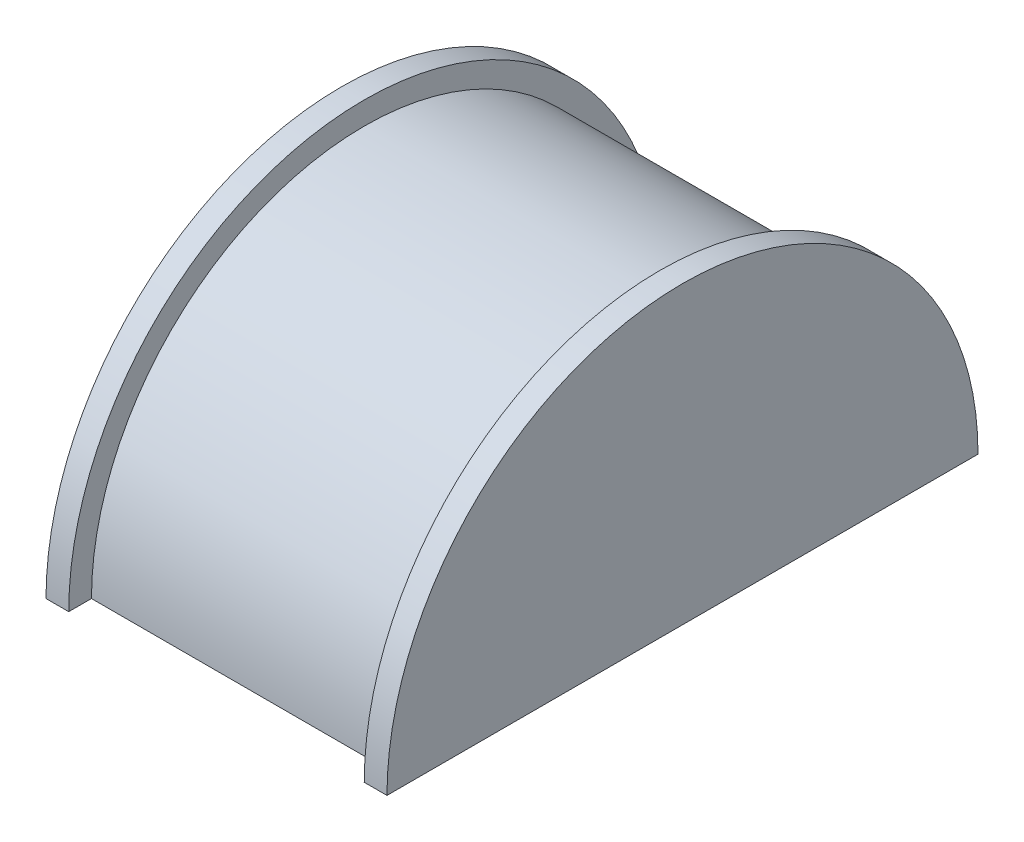
SolidWorks part; units mm, degrees
ref_plane "Front Plane" through (0, 0, 0) normal (0, 0, 1) x (1, 0, 0)
ref_plane "Top Plane" through (0, 0, 0) normal (0, 1, 0) x (1, 0, 0)
ref_plane "Right Plane" through (0, 0, 0) normal (1, 0, 0) x (0, 0, -1)
sketch "Sketch2" plane through (0, 0, 0) normal (1, 0, 0) x (0, 0, -1)
  line L0 (-6, 0) -> (6, 0)
  arc A0 (6, 0) -> (-6, 0) centre (0, 0) ccw
  dimension "D1" = 12
extrude "Boss-Extrude1" add sketch "Sketch2" along normal blind 6.5
ref_plane "Plane1" through (3.25, 0, 0) normal (1, 0, 0) x (0, 0, -1)
sketch "Sketch3" plane through (6.5, 0, 0) normal (1, 0, 0) x (0, 0, -1)
  line L0 (-6, 0) -> (6, 0) construction
  line L1 (-6.5, 0) -> (6.5, 0)
  arc A0 (6.5, 0) -> (-6.5, 0) centre (0, 0) ccw
  arc A1 (6, 0) -> (-6, 0) centre (0, 0) ccw construction
  dimension "D1" = 0.5
extrude "Boss-Extrude2" add sketch "Sketch3" along normal blind 0.5
mirror "Mirror1" about plane through (3.25, 0, 0) normal (1, 0, 0) of "Boss-Extrude2"
sketch "Sketch4" plane through (0, 0, 0) normal (0, -1, 0) x (1, 0, 0)
  line L0 (3.25, -6) -> (3.25, 6) construction
  line L1 (6.5, -6) -> (0, -6) construction
  line L2 (6.5, 6) -> (0, 6) construction
  circle A0 centre (3.25, 0) radius 1.9
  dimension "D1" = 3.8
extrude "Cut-Extrude1" cut sketch "Sketch4" against normal blind 5
equation "\"X-ROD-SPACING\"=45"
equation "\"Y-ROD-SPACING\"=75"
equation "\"Z-ROD-SPACING\"=17.5"
equation "\"Y-BED-OFFSET\"=2"
equation "\"Y-BED-ROD-INSET\"=3.5"
equation "\"Y-BED-SCREW-SPACING\"=209"
equation "\"Y-BED-SCREW-CUTOUT-SLOT-HEIGHT\"=2.5"
equation "\"T-SLOT-NUT-FILLET-RADIUS\"=0.5"
equation "\"T-SLOT-SCREW-SHAFT-RADIUS\"=1.55"
equation "\"T-SLOT-SCREW-SHAFT-CUTOUT-LENGTH\"=11"
equation "\"T-SLOT-NUT-DEPTH\"=3.5"
equation "\"T-SLOT-NUT-WIDTH\"=2.85"
equation "\"T-SLOT-NUT-END-DISTANCE\"=8"
equation "\"ACRYLIC-THICKNESS\"=10"
equation "\"ACRYLIC-THICKNESS2\"=4.5"
equation "\"ACRYLIC-TAB-CUTOUT-SIZE\"=\"ACRYLIC-THICKNESS\"+\"ACRYLIC-TAB-TOLERANCE\"*2"
equation "\"ACRYLIC-TAB-TOLERANCE\"=-.05"
equation "\"KERF\"=0.075"
equation "\"ACRYLIC-THICKNESS-TAB-CUTOUT-WIDTH\"=\"ACRYLIC-THICKNESS\"-\"KERF\"*2"
equation "\"ACRYLIC-THICKNESS-TAB-CUTOUT-HEIGHT\"=\"ACRYLIC-TAB-WIDTH\"-\"KERF\"*4"
equation "\"ACRYLIC-THICKNESS2-TAB-CUTOUT-WIDTH\"=\"ACRYLIC-THICKNESS2\"-\"KERF\"*2"
equation "\"ACRYLIC-THICKNESS2-TAB-CUTOUT-HEIGHT\"=\"ACRYLIC-TAB-WIDTH\"-\"KERF\"*4"
equation "\"ACRYLIC-TAB-WIDTH\"=\"ACRYLIC-THICKNESS\""
equation "\"ACRYLIC-M3-HOLE\"=2.9"
equation "\"SMOOTHROD-CAP-SCREW-DISTANCE\"=20"
equation "\"FRAME-WIDTH-INNER\"=370"
equation "\"NEMA17-HOLE-SPACING\"=31"
equation "\"NEMA17-CENTRAL-CUTOUT\"=22.5"
equation "\"Z-BRACKET-REACH\"=57"
equation "\"Z-ROD-INSET\"=13.5"
equation "\"TOP-BRACKET-SPACING\"=40"
equation "\"SMOOTHROD-X-LENGTH\"=350"
equation "\"SMOOTHROD-Y-LENGTH\"=350"
equation "\"SMOOTHROD-Z-LENGTH\"=350"
equation "\"SMOOTHROD-TIGHTENING-HEADROOM\"=.25"
equation "\"LEADSCREW-Z-LENGTH\"=300"
equation "\"SCREW-LENGTH-FRAME\"=\"ACRYLIC-THICKNESS\" + 10"
equation "\"SCREW-LENGTH-MOTOR\"=\"ACRYLIC-THICKNESS\" + 5"
equation "\"SCREW-LENGTH-EXTRUDER\"=28"
equation "\"SCREW-HEAD-RADIUS\"=6"
equation "\"PRINTED-M3-HOLE\"=3.5"
equation "\"PRINTED-X-SMOOTHROD-DIAMETER\"=8.8"
equation "\"PRINTED-X-SMOOTHROD-CUTOUT\"=10"
equation "\"PRINTED-X-BASE-HEIGHT\"=10"
equation "\"PRINTED-LM8UU-CUTOUT-SIZE\"=15.5"
equation "\"PRINTED-LM8UU-CUTOUT-LENGTH\"=24.5"
equation "\"PRINTED-X-IDLER-HEIGHT\"=16"
equation "\"PRINTED-M3-NUT-AF\"=6.25"
equation "\"PSU-MOUNTING-WIDTH\"=95"
equation "\"PSU-MOUNTING-HEIGHT\"=177"
equation "\"Y-BELT-TO-ROD-DISTANCE\"=20"
equation "\"SPOOL-HOLDER-ROD-SPACING\"=150"
equation "\"ACRYLIC-X-CARRIAGE-WIDTH\"=55"
equation "\"ACRYLIC-X-CARRIAGE-HEIGHT\"=75"
equation "\"ACRYLIC-X-CARRIAGE-LM8UU-CUTOUT-WIDTH\"=24.25"
equation "\"ACRYLIC-X-CARRIAGE-LM8UU-CUTOUT-HEIGHT\"=11.0"
equation "\"ACRYLIC-X-CARRIAGE-SCREW-SPACING-X\"=15"
equation "\"ACRYLIC-X-CARRIAGE-SCREW-SPACING-Y\"=33"
equation "\"ACRYLIC-X-CARRIAGE-CENTER-TAB-SPACING\"=14"
equation "\"ACRYLIC-X-CARRIAGE-EXTRUDER-OFFSET\"=26"
equation "\"ACRYLIC-X-CARRIAGE-EXTRUDER-ANGLE\"=90"
equation "\"ACRYLIC-X-CARRIAGE-EXTRUDER-SHELF-DEPTH\"=\"ACRYLIC-X-CARRIAGE-EXTRUDER-OFFSET\" + 28"
equation "\"ACRYLIC-X-CARRIAGE-EXTRUDER-BRACE-SPACING\"=23"
equation "\"ACRYLIC-X-CARRIAGE-EXTRUDER-BRACE-TAB-OFFSET\"=20"
equation "\"ACRYLIC-X-CARRIAGE-EXTRUDER-BRACE-HEIGHT\"=35"
equation "\"ACRYLIC-X-CARRIAGE-EXTRUDER-BRACE-SCREW-SPACING\"=22"
equation "\"ACRYLIC-X-CARRIAGE-DUAL-WIDTH-MULTIPLIER\"=1.65"
equation "\"ACRYLIC-X-CARRIAGE-DUAL-HOTEND-SPACING\"=42"
equation "\"ACRYLIC-X-CARRIAGE-DUAL-WIDTH\"=75"
equation "\"ACRYLIC-X-CARRIAGE-DUAL-FAN-OFFSET\"=52"
equation "\"ACRYLIC-X-CARRIAGE-DUAL-FAN-HEIGHT\"=20"
equation "\"ACRYLIC-X-CARRIAGE-DUAL-HOTEND-SEPARATION\"=36"
equation "\"ACRYLIC-X-CARRIAGE-DUAL-MOUNT-PLATE-DEPTH\"=75"
equation "\"ACRYLIC-X-CARRIAGE-DUAL-MOUNT-BRACE-WIDTH\"=33"
equation "\"ACRYLIC-X-CARRIAGE-DUAL-MOUNT-SCREW-WIDTH\"=40"
equation "\"BLOWER-FAN-WIDTH\"=15"
